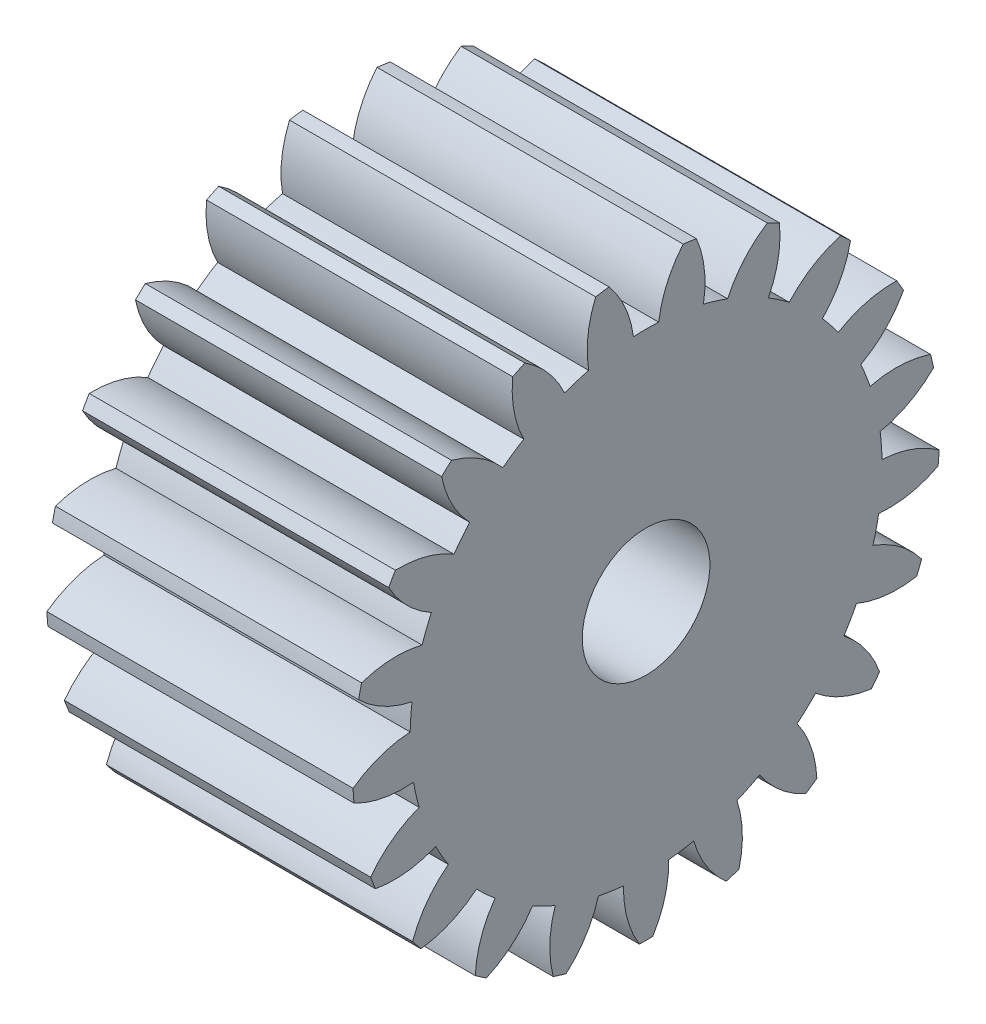
SolidWorks part; units mm, degrees
ref_plane "Plane1" through (0, 0, 0) normal (0, 0, 1) x (1, 0, 0)
ref_plane "Plane2" through (0, 0, 0) normal (0, 1, 0) x (1, 0, 0)
ref_plane "Plane3" through (0, 0, 0) normal (1, 0, 0) x (0, 0, -1)
other "Configuration Table"
sketch "HoldingSke" plane through (0, 0, 0) normal (0, 1, 0) x (1, 0, 0)
  line L0 (0, 0) -> (0.9336, -0.3584)
  line L1 (-15, 0) -> (100, 0) construction
  line L2 (0, 0) -> (-2.1039, 2.3779)
  line L3 (0, 0) -> (-11.863, 4.5341)
  line L4 (0, 0) -> (8.0624, 3.0949)
  line L5 (0, 0) -> (-46.8476, -17.4728)
  line L6 (0, 0) -> (-7.4607, -5.0337)
  line L7 (-2.1039, 2.3779) -> (8.6586, 51.2059)
  line L8 (-76.2, 54.61) -> (-75.3, 54.61)
  line L9 (-71.009, 38.7566) -> (-53.1078, 45.2721)
  line L10 (-76.2, 71.12) -> (104.1128, 71.12)
  line L11 (0, 0) -> (-9, 0)
  line L12 (-76.2, 101.6) -> (-76.162, 101.6)
  line L13 (24.9733, 27.94) -> (52.9518, 28.4284)
  line L14 (24.9733, 27.94) -> (24.9743, 27.94)
  line L15 (24.9733, 27.94) -> (100.4006, 29.5858)
  line L16 (-63.627, -1) -> (-12.827, -1)
  circle A0 centre (0, 0) radius 2.5
  circle A1 centre (0, 0) radius 9.249
  circle A2 centre (0, 0) radius 37.5
  circle A3 centre (0, 0) radius 2.5
  dimension "MHD" = 18.498
  dimension "Hub_dia" = 75
  dimension "Bore" = 5
  dimension "MBD" = 5
  dimension "Num_teeth" = 21
  dimension "Pitch" = 1
  dimension "Overall_len" = 50
  dimension "Show_teeth" = 21
  dimension "Thickness" = 9
  dimension "OAL" = 50.0001
  dimension "T_dim" = 0.9
  dimension "Ap" = 20
  dimension "H" = 19.05
  dimension "Pitch_radius" = 180.3128
  dimension "Width" = 9
  dimension "Backlash" = 0.038
  dimension "Addendum_fac" = 1
  dimension "Dedendum_fac" = 1.25
  dimension "Clearance_fac" = 0.25
  dimension "Dedendum_add" = 0.001
  dimension "Module" = 1
sketch "BasProSke" plane through (0, 0, 0) normal (0, 1, 0) x (1, 0, 0)
  line L0 (-10, 0) -> (60, 0) construction
  line L1 (0, 0) -> (0, 11.5)
  line L2 (0, 0) -> (12, 0)
  line L3 (12, 0) -> (12, 11.5)
  line L4 (12, 11.5) -> (0, 11.5)
  dimension "Thickness" = 12
  dimension "Diameter" = 23
revolve "Base-Revolve" add sketch "BasProSke" angle 360 about L0
sketch "TooCutSke" plane through (0, 0, 0) normal (1, 0, 0) x (0, 0, -1)
  line L1 (0, 0) -> (0, 107) construction
  line L2 (0, 0) -> (-0.8511, 10.4654) construction
  line L3 (0, 0) -> (-3.1226, 20.7168) construction
  line L4 (-0.8511, 10.4654) -> (-1.5613, 10.3584) construction
  arc A0 (0.4953, 9.2357) -> (-0.4953, 9.2357) centre (0, 0) ccw
  arc A1 (1.4725, 11.431) -> (-1.4725, 11.431) centre (0, 0) ccw
  circle A2 centre (0, 0) radius 10.5 construction
  circle A3 centre (0, 0) radius 9.8668 construction
  arc A4 (-0.4953, 9.2357) -> (-1.4725, 11.431) centre (-4.6605, 8.6967) ccw
  arc A5 (1.4725, 11.431) -> (0.4953, 9.2357) centre (4.6605, 8.6967) ccw
  dimension "Root_dia" = 18.498
  dimension "Overcut_dia" = 23.0508
  dimension "Pitch_dia" = 21
  dimension "Base_dia" = 19.7335
  dimension "Flank_rad" = 4.2
  dimension "Half_ang" = 8.571
  dimension "Half_CT" = 0.7182
extrude "ToothCut" cut sketch "TooCutSke" along normal through all
fillet "Breaks" [suppressed] radius 0.02
fillet "RootFillets" [suppressed] radius 0.251
pattern_circular "TeethCuts" count 21 every 17.143 about axis through (-10, 0, 0) along (1, 0, 0) of "ToothCut", "RootFillets", "Breaks"
sketch "HubNeaOneSke" plane through (0, 0, 0) normal (-1, 0, 0) x (0, 0, 1)
  circle A0 centre (0, 0) radius 9.249
  dimension "Diameter" = 18.498
extrude "HubNearOne" [suppressed] add sketch "HubNeaOneSke" along normal blind 38.0001
sketch "HubNeaBotSke" plane through (0, 0, 0) normal (-1, 0, 0) x (0, 0, 1)
  circle A0 centre (0, 0) radius 9.249
  dimension "Diameter" = 18.498
extrude "HubNearBoth" [suppressed] add sketch "HubNeaBotSke" along normal blind 19
ref_plane "FarPln" through (12, 0, 0) normal (1, 0, 0) x (0, 0, -1)
sketch "HubFarSke" plane through (12, 0, 0) normal (1, 0, 0) x (0, 0, -1)
  circle A0 centre (0, 0) radius 9.249
  dimension "Diameter" = 18.498
extrude "HubFar" [suppressed] add sketch "HubFarSke" along normal blind 19
sketch "BorSke" plane through (0, 0, 0) normal (1, 0, 0) x (0, 0, -1)
  circle A0 centre (0, 0) radius 2.5
  dimension "Diameter" = 5
extrude "Bore" cut sketch "BorSke" along normal mid plane 100.0001
sketch "KeySke" plane through (0, 0, 0) normal (1, 0, 0) x (0, 0, -1)
  line L0 (-1, 0) -> (-1, 3.4)
  line L1 (-1, 3.4) -> (1, 3.4)
  line L2 (1, 3.4) -> (1, 0)
  line L3 (0, 0) -> (0, 34) construction
  line L4 (-1, 0) -> (1, 0)
  dimension "Offset" = 3.4
  dimension "Width" = 2
extrude "Keyway" [suppressed] cut sketch "KeySke" along normal mid plane 100.0001
pattern_circular "Keyway2" [suppressed] count 2 every 90 about axis through (-10, 0, 0) along (1, 0, 0)
equation "' \"Module@HoldingSke\" = 6.35"
equation "' \"Num_teeth@HoldingSke\" = 12"
equation "' \"Ap@HoldingSke\" =  20"
equation "' \"Ap@HoldingSke\" = 20"
equation "' \"Width@HoldingSke\" = 0.5 * 25.4"
equation "' \"Hub_dia@HoldingSke\"= 1 * 25.4"
equation "' \"Hub_dia@HoldingSke\" = 1 * 25.4"
equation "' \"Overall_len@HoldingSke\" = 1.0 * 25.4"
equation "' \"Bore@HoldingSke\" = 0.75 * 25.4"
equation "' \"T_dim@HoldingSke\" = 0.1 * 25.4"
equation "' \"Width@KeySke\" = 0.25 * 25.4"
equation "' \"Show_teeth@HoldingSke\" = 13"
equation "' \"Backlash@HoldingSke\" = 0.009 * 25.4"
equation "' \"Addendum_fac@HoldingSke\" = 1.0"
equation "' \"Dedendum_fac@HoldingSke\" = 1.25"
equation "' \"Dedendum_add@HoldingSke\" = 0.00005 * 25.4"
equation "' \"Clearance_fac@HoldingSke\" = 0.25"
equation "\"Pitch@HoldingSke\" = 1 / \"Module@HoldingSke\""
equation "\"Overcut_dia@TooCutSke\" = (\"Num_teeth@HoldingSke\" + 2 * \"Addendum_fac@HoldingSke\") / \"Pitch@HoldingSke\" + 0.002 * 25.4"
equation "\"Pitch_dia@TooCutSke\" = \"Num_teeth@HoldingSke\" / \"Pitch@HoldingSke\""
equation "\"Base_dia@TooCutSke\" = \"Num_teeth@HoldingSke\" / \"Pitch@HoldingSke\" * cos((\"Ap@HoldingSke\"  * 3.14159265 / 180))"
equation "\"Root_dia@TooCutSke\" = (\"Num_teeth@HoldingSke\" + 2) / \"Pitch@HoldingSke\" - 2 * (\"Addendum_fac@HoldingSke\" + \"Dedendum_fac@HoldingSke\") / \"Pitch@HoldingSke\" - \"Dedendum_add@HoldingSke\" * 2"
equation "\"Half_ang@TooCutSke\" = 180 / \"Num_teeth@HoldingSke\""
equation "\"Half_CT@TooCutSke\" = \"Num_teeth@HoldingSke\" / \"Pitch@HoldingSke\" * sin((3.14159265 / 2 / \"Num_teeth@HoldingSke\")) / 2 - 7 * \"Backlash@HoldingSke\" / 4"
equation "\"Flank_rad@TooCutSke\" = \"Num_teeth@HoldingSke\" / \"Pitch@HoldingSke\" / 5"
equation "\"Radius@RootFillets\" = \"Clearance_fac@HoldingSke\" / \"Pitch@HoldingSke\" + \"Dedendum_add@HoldingSke\""
equation "\"Break_rad@Breaks\" = 0.02 / \"Pitch@HoldingSke\""
equation "\"Thickness@HoldingSke\" = \"Width@HoldingSke\""
equation "\"OAL@HoldingSke\" = \"Thickness@HoldingSke\""
equation "\"MHD@HoldingSke\" = (\"Num_teeth@HoldingSke\" + 2) / \"Pitch@HoldingSke\" - 2 * (\"Addendum_fac@HoldingSke\" + \"Dedendum_fac@HoldingSke\")  / \"Pitch@HoldingSke\" - \"Dedendum_add@HoldingSke\" * 2"
equation "\"MBD@HoldingSke\" = (\"Num_teeth@HoldingSke\" + 2) / \"Pitch@HoldingSke\" - 2 * (\"Addendum_fac@HoldingSke\" + \"Dedendum_fac@HoldingSke\")  / \"Pitch@HoldingSke\" - \"Dedendum_add@HoldingSke\" * 2 - 0.002 * 25.4"
equation "\"MHD@HoldingSke\" = ((sgn( \"MHD@HoldingSke\" - \"Hub_dia@HoldingSke\" )-1)*( \"MHD@HoldingSke\" - \"Hub_dia@HoldingSke\" ))/-2+ \"Hub_dia@HoldingSke\""
equation "\"MBD@HoldingSke\" = ((sgn( \"MBD@HoldingSke\" - \"Bore@HoldingSke\" )-1)*( \"MBD@HoldingSke\" - \"Bore@HoldingSke\" ))/-2+ \"Bore@HoldingSke\""
equation "\"OAL@HoldingSke\" = ((sgn( \"OAL@HoldingSke\" - \"Overall_len@HoldingSke\" )+1)*( \"OAL@HoldingSke\" - \"Overall_len@HoldingSke\" ))/2 + \"Overall_len@HoldingSke\" + 0.000002 * 25.4"
equation "\"Num_teeth@TeethCuts\" = int( \"Show_teeth@HoldingSke\" ) + 1"
equation "\"Num_teeth@TeethCuts\" = ((sgn( \"Num_teeth@TeethCuts\" - \"Num_teeth@HoldingSke\" )-1)*( \"Num_teeth@TeethCuts\" - \"Num_teeth@HoldingSke\" ))/-2+ \"Num_teeth@HoldingSke\""
equation "\"Num_teeth@TeethCuts\" = ((sgn( \"Num_teeth@TeethCuts\" - 2.0)+1)*( \"Num_teeth@TeethCuts\" - 2.0))/2 +2.0"
equation "\"Angle@TeethCuts\" = 360.0 / \"Num_teeth@HoldingSke\""
equation "\"Diameter@BasProSke\" = (\"Num_teeth@HoldingSke\" + 2 * \"Addendum_fac@HoldingSke\") / \"Pitch@HoldingSke\""
equation "\"Thickness@BasProSke\"=12"
equation "' \"Fillet_rad@BasProSke\" =  \"Thickness@HoldingSke\" * 0.05"
equation "' \"Fillet_rad@BasProSke\" = \"Thickness@HoldingSke\" * 0.05"
equation "\"MHD@HoldingSke\" = ((sgn( \"MHD@HoldingSke\" - \"Root_dia@TooCutSke\" )-1)*( \"MHD@HoldingSke\" - \"Root_dia@TooCutSke\" ))/-2+ \"Root_dia@TooCutSke\""
equation "\"Diameter@HubNeaOneSke\" = \"MHD@HoldingSke\""
equation "\"Length@HubNearOne\" = \"OAL@HoldingSke\" - \"Thickness@BasProSke\""
equation "\"Diameter@HubNeaBotSke\" = \"MHD@HoldingSke\""
equation "\"Length@HubNearBoth\" = ( \"OAL@HoldingSke\" - \"Thickness@BasProSke\" ) / 2.0"
equation "\"Thickness@FarPln\" = \"Thickness@BasProSke\""
equation "\"Diameter@HubFarSke\" = \"MHD@HoldingSke\""
equation "\"Length@HubFar\" = ( \"OAL@HoldingSke\" - \"Thickness@BasProSke\" ) / 2.0"
equation "\"Diameter@BorSke\" = \"MBD@HoldingSke\""
equation "\"D1@Bore\" = \"OAL@HoldingSke\" * 2.0"
equation "\"D1@Keyway\" = \"OAL@HoldingSke\" * 2.0"
equation "\"Offset@KeySke\" = \"T_dim@HoldingSke\" + \"MBD@HoldingSke\" / 2.0"
